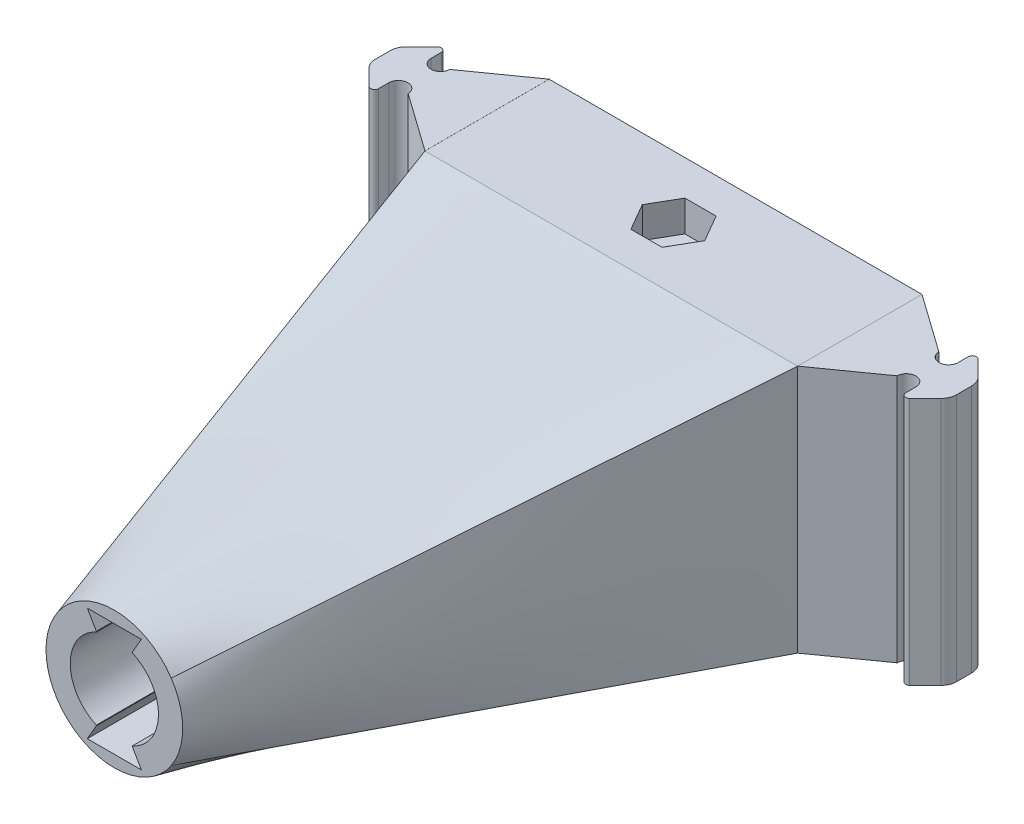
SolidWorks part; units mm, degrees
ref_plane "Front" through (0, 0, 0) normal (0, 0, 1) x (1, 0, 0)
ref_plane "Top" through (0, 0, 0) normal (0, 1, 0) x (1, 0, 0)
ref_plane "Right" through (0, 0, 0) normal (1, 0, 0) x (0, 0, -1)
sketch "Sketch1" plane through (0, 0, 0) normal (0, 0, 1) x (1, 0, 0)
  line L1 (0, 0) -> (76.2, 0)
  line L2 (0, 0) -> (0, 50.8)
  line L3 (0, 50.8) -> (76.2, 50.8)
  line L4 (76.2, 0) -> (76.2, 50.8)
  dimension "D1" = 76.2
  dimension "D2" = 50.8
ref_plane "Plane1" through (0, 0, 101.6) normal (0, 0, 1) x (1, 0, 0)
sketch "Sketch2" plane through (0, 0, 101.6) normal (0, 0, 1) x (1, 0, 0)
  line L0 (0, 0) -> (0, 50.8) construction
  line L1 (0, 50.8) -> (76.2, 50.8) construction
  circle A0 centre (38.1, 25.4) radius 13.97
  point P4 (0, 25.4)
  point P7 (38.1, 50.8)
  dimension "D1" = 27.94
loft "Loft1" add profiles "Sketch2", "Sketch1"
sketch "Sketch3" plane through (0, 0, 101.6) normal (0, 0, 1) x (1, 0, 0)
  line L0 (34.925, 33.909) -> (34.925, 33.2945) construction
  line L1 (41.275, 33.2945) -> (41.275, 33.909) construction
  line L2 (41.275, 33.909) -> (42.7415, 36.449) construction
  line L3 (42.7415, 36.449) -> (33.4585, 36.449) construction
  line L4 (33.4585, 36.449) -> (34.925, 33.909) construction
  line L5 (34.925, 33.909) -> (41.275, 33.909) construction
  line L6 (34.925, 16.891) -> (34.925, 17.5055) construction
  line L7 (41.275, 16.891) -> (41.275, 17.5055) construction
  line L8 (34.925, 16.891) -> (41.275, 16.891) construction
  line L9 (34.925, 16.891) -> (33.4585, 14.351) construction
  line L10 (33.4585, 14.351) -> (42.7415, 14.351) construction
  line L11 (42.7415, 14.351) -> (41.275, 16.891) construction
  line L12 (34.417, 33.7729) -> (34.417, 33.6305)
  line L13 (34.417, 17.0271) -> (34.417, 17.1695)
  line L14 (41.783, 17.0271) -> (41.783, 17.1695)
  line L15 (41.783, 33.6305) -> (41.783, 33.7729)
  line L16 (41.783, 33.7729) -> (43.6214, 36.957)
  line L17 (43.6214, 36.957) -> (32.5786, 36.957)
  line L18 (32.5786, 36.957) -> (34.417, 33.7729)
  line L19 (34.417, 17.0271) -> (32.5786, 13.843)
  line L20 (32.5786, 13.843) -> (43.6214, 13.843)
  line L21 (43.6214, 13.843) -> (41.783, 17.0271)
  line L22 (32.5786, 36.957) -> (34.4851, 33.655) construction
  line L23 (34.925, 16.383) -> (41.275, 16.383)
  line L24 (34.417, 33.909) -> (34.417, 33.6305) construction
  line L25 (41.783, 33.6305) -> (41.783, 33.909) construction
  line L26 (41.7149, 33.655) -> (43.6214, 36.957) construction
  line L27 (41.783, 16.891) -> (41.783, 17.1695) construction
  line L28 (43.6214, 13.843) -> (41.7149, 17.145) construction
  line L29 (34.4851, 17.145) -> (32.5786, 13.843) construction
  line L30 (34.417, 16.891) -> (34.417, 17.1695) construction
  arc A0 (34.925, 33.2945) -> (34.925, 17.5055) centre (38.1, 25.4) ccw construction
  arc A1 (49.7237, 33.1492) -> (26.4763, 33.1492) centre (38.1, 25.4) ccw construction
  arc A2 (41.275, 17.5055) -> (41.275, 33.2945) centre (38.1, 25.4) ccw construction
  arc A3 (34.417, 33.6305) -> (34.417, 17.1695) centre (38.1, 25.4) ccw
  arc A4 (41.783, 17.1695) -> (41.783, 33.6305) centre (38.1, 25.4) ccw
  point P9 (38.1, 33.909)
  dimension "D1" = 17.018
  dimension "D2" = 60
  dimension "D3" = 60
  dimension "D4" = 6.35
  dimension "D5" = 2.54
  dimension "D6" = 2.54
  dimension "D7" = 60
  dimension "D8" = 60
  dimension "D9" = 0.508
extrude "Cut-Extrude1" cut sketch "Sketch3" against normal blind 88.9
sketch "Sketch4" plane through (0, 0, 12.7) normal (0, 0, 1) x (1, 0, 0)
  circle A0 centre (38.1, 25.4) radius 5.715
  arc A1 (34.417, 33.6305) -> (34.417, 17.1695) centre (38.1, 25.4) ccw construction
  dimension "D1" = 11.43
extrude "Cut-Extrude2" cut sketch "Sketch4" against normal through all
sketch "Sketch5" plane through (0, 0, 0) normal (0, 0, -1) x (-1, 0, 0)
  line L1 (-76.2, 50.8) -> (0, 50.8)
  line L2 (-76.2, 50.8) -> (-76.2, 0)
  line L3 (-76.2, 0) -> (0, 0)
  line L4 (0, 50.8) -> (0, 0)
extrude "Boss-Extrude1" add sketch "Sketch5" along normal blind 25.4
sketch "Sketch8" plane through (0, 0, 0) normal (0, -1, 0) x (1, 0, 0)
  line L0 (91.9667, -8.38) -> (91.9667, -6.3031)
  line L1 (93.3653, -5.7232) -> (96.5694, -8.9227)
  line L2 (97.4907, -11.1446) -> (97.4907, -14.2554)
  line L3 (96.5694, -16.4773) -> (93.3653, -19.6768)
  line L4 (91.9667, -19.0969) -> (91.9667, -17.02)
  line L5 (88.0731, -8.4342) -> (76.2, 0)
  line L6 (76.2, 0) -> (76.2, -25.4)
  line L7 (76.2, -25.4) -> (88.0731, -16.9658)
  line L8 (0, -25.4) -> (0, 0) construction
  line L10 (38.1, 0) -> (38.1, -25.4) construction
  line L11 (0, 0) -> (76.2, 0) construction
  line L12 (76.2, -25.4) -> (0, -25.4) construction
  line L13 (0, -25.4) -> (-11.8731, -16.9658)
  line L14 (0, 0) -> (0, -25.4)
  line L15 (-11.8731, -8.4342) -> (0, 0)
  line L16 (-15.7667, -19.0969) -> (-15.7667, -17.02)
  line L17 (-20.3694, -16.4773) -> (-17.1653, -19.6768)
  line L18 (-21.2907, -11.1446) -> (-21.2907, -14.2554)
  line L19 (-17.1653, -5.7232) -> (-20.3694, -8.9227)
  line L20 (-15.7667, -8.38) -> (-15.7667, -6.3031)
  arc A0 (91.9667, -17.02) -> (88.0731, -16.9658) centre (90.0195, -17.02) ccw
  arc A1 (88.0731, -8.4342) -> (91.9667, -8.38) centre (90.0195, -8.38) ccw
  arc A2 (91.9667, -6.3031) -> (93.3653, -5.7232) centre (92.7862, -6.3031) cw
  arc A3 (96.5694, -8.9227) -> (97.4907, -11.1446) centre (94.3508, -11.1446) cw
  arc A4 (97.4907, -14.2554) -> (96.5694, -16.4773) centre (94.3508, -14.2554) cw
  arc A5 (93.3653, -19.6768) -> (91.9667, -19.0969) centre (92.7862, -19.0969) cw
  arc A6 (-17.1653, -19.6768) -> (-15.7667, -19.0969) centre (-16.5862, -19.0969) ccw
  arc A7 (-21.2907, -14.2554) -> (-20.3694, -16.4773) centre (-18.1508, -14.2554) ccw
  arc A8 (-20.3694, -8.9227) -> (-21.2907, -11.1446) centre (-18.1508, -11.1446) ccw
  arc A9 (-15.7667, -6.3031) -> (-17.1653, -5.7232) centre (-16.5862, -6.3031) ccw
  arc A10 (-11.8731, -8.4342) -> (-15.7667, -8.38) centre (-13.8195, -8.38) cw
  arc A11 (-15.7667, -17.02) -> (-11.8731, -16.9658) centre (-13.8195, -17.02) cw
  point P18 (97.4907, -12.7)
  point P23 (76.2, -12.7)
  dimension "D1" = 3.14
  dimension "D4" = 0.8195
  dimension "D6" = 1.9472
  dimension "D2" = 3.1108
  dimension "D3" = 4.528
  dimension "D5" = 2.0769
  dimension "D7" = 88.0731
  dimension "D8" = 90.0195
  dimension "D9" = 93.3653
extrude "Boss-Extrude3" add sketch "Sketch8" against normal through all
sketch "Sketch9" plane through (0, 0, 12.7) normal (0, 0, 1) x (1, 0, 0)
  circle A0 centre (38.1, 25.4) radius 7.747
  arc A1 (41.783, 17.1695) -> (41.783, 33.6305) centre (38.1, 25.4) ccw construction
  circle A2 centre (38.1, 25.4) radius 6.731
  dimension "D1" = 15.494
  dimension "D2" = 13.462
extrude "Cut-Extrude3" cut sketch "Sketch9" against normal blind 2.54
sketch "Sketch10" plane through (0, 50.8, 0) normal (0, 1, 0) x (1, 0, 0)
  line L0 (0, 25.4) -> (76.2, 25.4) construction
  line L1 (31.7209, 12.7) -> (34.9104, 7.1755)
  line L2 (34.9104, 7.1755) -> (41.2896, 7.1755)
  line L3 (41.2896, 7.1755) -> (44.4791, 12.7)
  line L4 (44.4791, 12.7) -> (41.2896, 18.2245)
  line L5 (41.2896, 18.2245) -> (34.9104, 18.2245)
  line L6 (34.9104, 18.2245) -> (31.7209, 12.7)
  line L7 (0, 25.4) -> (0, 0) construction
  circle A0 centre (38.1, 12.7) radius 5.5245 construction
  point P10 (38.1, 25.4)
  point P13 (0, 12.7)
  dimension "D1" = 11.049
extrude "Cut-Extrude4" cut sketch "Sketch10" against normal blind 6.35
ref_plane "Plane2" through (0, 25.4, 0) normal (0, -1, 0) x (-1, 0, 0)
mirror "Mirror1" about plane through (0, 25.4, 0) normal (0, -1, 0) of "Cut-Extrude4"
sketch "Sketch11" plane through (0, 44.45, 0) normal (0, 1, 0) x (1, 0, 0)
  line L0 (0, 25.4) -> (76.2, 25.4) construction
  line L1 (0, 25.4) -> (0, 0) construction
  circle A0 centre (38.1, 12.7) radius 3.175
  point P4 (38.1, 25.4)
  point P7 (0, 12.7)
  dimension "D1" = 6.35
extrude "Cut-Extrude5" cut sketch "Sketch11" against normal through all
